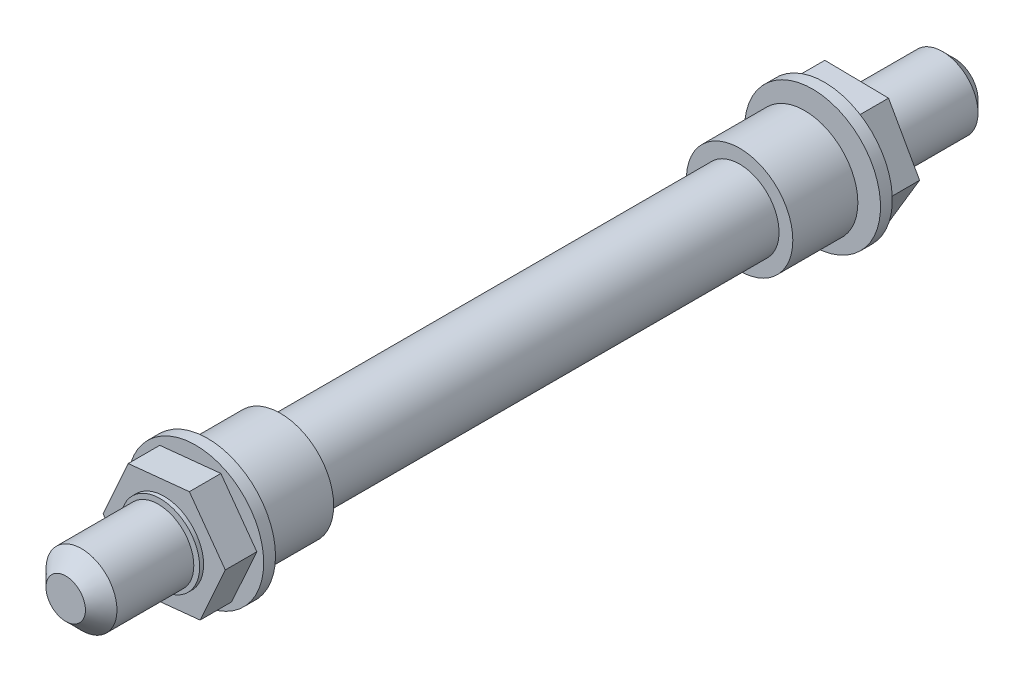
SolidWorks part; units mm, degrees
ref_plane "前视基准面" through (0, 0, 0) normal (0, 0, 1) x (1, 0, 0)
ref_plane "上视基准面" through (0, 0, 0) normal (0, 1, 0) x (1, 0, 0)
ref_plane "右视基准面" through (0, 0, 0) normal (1, 0, 0) x (0, 0, -1)
sketch "草图1" plane through (0, 0, 0) normal (0, 0, 1) x (1, 0, 0)
  circle A0 centre (0, 0) radius 10
  dimension "D1" = 20
extrude "凸台-拉伸1" add sketch "草图1" along normal mid plane 116.5
sketch "草图2" plane through (0, 0, 58.25) normal (0, 0, 1) x (1, 0, 0)
  circle A0 centre (0, 0) radius 13.5
  dimension "D1" = 27
extrude "凸台-拉伸2" add sketch "草图2" along normal blind 16.5
sketch "草图3" plane through (0, 0, 74.75) normal (0, 0, 1) x (1, 0, 0)
  circle A0 centre (0, 0) radius 10
  dimension "D1" = 20
extrude "凸台-拉伸3" add sketch "草图3" along normal blind 14
sketch "草图4" plane through (0, 0, 88.75) normal (0, 0, 1) x (1, 0, 0)
  circle A0 centre (0, 0) radius 3
  dimension "D1" = 6
extrude "凸台-拉伸4" add sketch "草图4" along normal blind 0.48
sketch "草图5" plane through (0, 0, 89.23) normal (0, 0, 1) x (1, 0, 0)
  circle A0 centre (0, 0) radius 9
  dimension "D1" = 18
extrude "凸台-拉伸5" add sketch "草图5" along normal blind 23.5
chamfer "倒角1" distance 4 angle 45 1 edges at (9, 0, 112.73)
ref_plane "基准面1" through (0, 0, 76.75) normal (0, 0, 1) x (1, 0, 0)
sketch "草图6" plane through (0, 0, 76.75) normal (0, 0, 1) x (1, 0, 0)
  circle A0 centre (0, 0) radius 17.25
  circle A1 centre (0, 0) radius 10.5
  dimension "D1" = 34.5
  dimension "D2" = 21
extrude "凸台-拉伸6" add sketch "草图6" along normal blind 3 separate body
sketch "草图7" plane through (0, 0, 79.75) normal (0, 0, 1) x (1, 0, 0)
  line L1 (6.3924, 14.2175) -> (-9.1165, 12.6447)
  line L2 (-9.1165, 12.6447) -> (-15.5089, -1.5728)
  line L3 (-15.5089, -1.5728) -> (-6.3924, -14.2175)
  line L4 (-6.3924, -14.2175) -> (9.1165, -12.6447)
  line L5 (9.1165, -12.6447) -> (15.5089, 1.5728)
  line L6 (15.5089, 1.5728) -> (6.3924, 14.2175)
  circle A0 centre (0, 0) radius 13.5 construction
  dimension "D1" = 27
extrude "凸台-拉伸7" add sketch "草图7" along normal blind 8
mirror "镜向3" about plane through (0, 0, 0) normal (0, 0, 1) of "凸台-拉伸2", "凸台-拉伸3", "凸台-拉伸4", "凸台-拉伸5"
chamfer "倒角2" distance 3 angle 45 1 edges at (9, 0, -112.73)
ref_plane "基准面2" through (0, 0, -76.75) normal (0, 0, -1) x (-1, 0, 0)
sketch "草图8" plane through (0, 0, -76.75) normal (0, 0, -1) x (-1, 0, 0)
  circle A0 centre (0, 0) radius 17.25
  circle A1 centre (0, 0) radius 17.25 construction
extrude "凸台-拉伸8" add sketch "草图8" along normal blind 3
sketch "草图9" plane through (0, 0, -79.75) normal (0, 0, -1) x (-1, 0, 0)
  line L1 (7.8787, 14.1159) -> (-8.2854, 13.8811)
  line L2 (-8.2854, 13.8811) -> (-16.1641, -0.2348)
  line L3 (-16.1641, -0.2348) -> (-7.8787, -14.1159)
  line L4 (-7.8787, -14.1159) -> (8.2854, -13.8811)
  line L5 (8.2854, -13.8811) -> (16.1641, 0.2348)
  line L6 (16.1641, 0.2348) -> (7.8787, 14.1159)
  circle A0 centre (0, 0) radius 14 construction
  dimension "D1" = 28
extrude "凸台-拉伸9" add sketch "草图9" along normal blind 8
